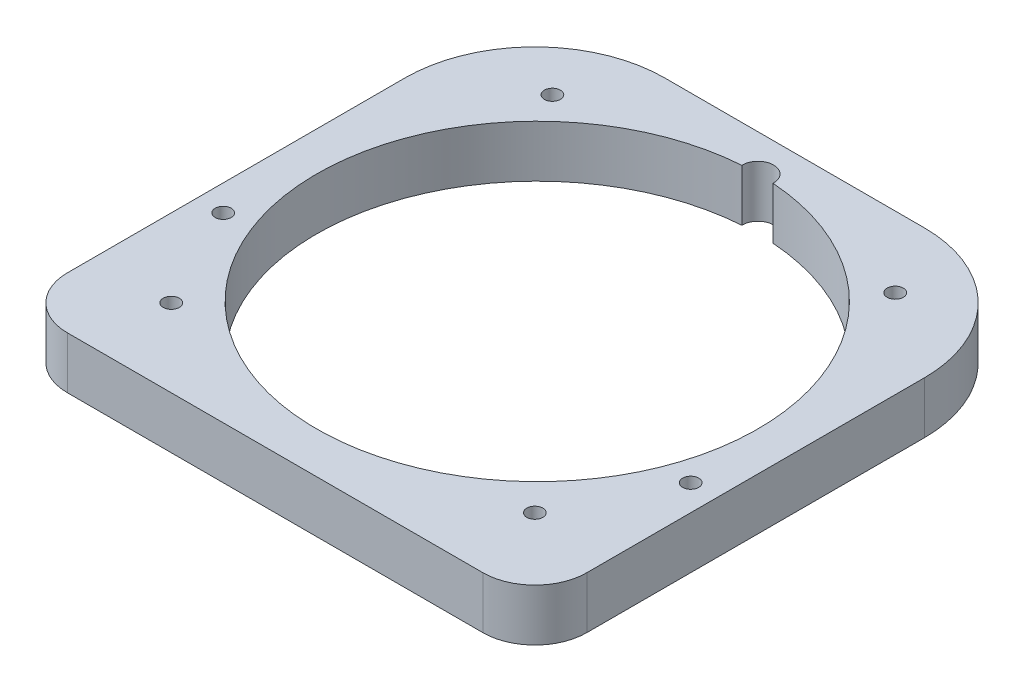
SolidWorks part; units mm, degrees
ref_plane "Płaszczyzna przednia" through (0, 0, 0) normal (0, 0, 1) x (1, 0, 0)
ref_plane "Płaszczyzna górna" through (0, 0, 0) normal (0, 1, 0) x (1, 0, 0)
ref_plane "Płaszczyzna prawa" through (0, 0, 0) normal (1, 0, 0) x (0, 0, -1)
sketch "Szkic1" plane through (0, 0, 0) normal (0, 1, 0) x (1, 0, 0)
  line L8 (10, 0) -> (90, 0)
  line L9 (100, 10) -> (100, 75)
  line L10 (75, 100) -> (25, 100)
  line L11 (0, 75) -> (0, 10)
  arc A8 (90, 0) -> (100, 10) centre (90, 10) ccw
  arc A9 (100, 75) -> (75, 100) centre (75, 75) ccw
  arc A10 (25, 100) -> (0, 75) centre (25, 75) ccw
  arc A11 (0, 10) -> (10, 0) centre (10, 10) ccw
extrude "Dodanie-wyciągnięcie1" add sketch "Szkic1" against normal blind 10
sketch "Szkic4" plane through (0, 0, 0) normal (0, 1, 0) x (1, 0, 0)
  line L0 (50, 15.022) -> (50, 78.4919) construction
  arc A0 (47.0019, 92.856) -> (52.9981, 92.856) centre (50, 50.4619) ccw
  arc A1 (52.9981, 92.856) -> (47.0019, 92.856) centre (50, 92.9619) ccw
  dimension "D3" = 85
  dimension "D4" = 6
  dimension "D1" = 0
  dimension "D2" = 6
extrude "Wytnij-wyciągnięcie2" cut sketch "Szkic4" against normal through all
sketch "Szkic5" plane through (0, 0, 0) normal (0, 1, 0) x (1, 0, 0)
  circle A0 centre (83, 86.3783) radius 1.55 construction
  circle A3 centre (85, 15) radius 1.55 construction
  circle A4 centre (83, 86.3783) radius 1.55
  circle A7 centre (85, 15) radius 1.55
  circle A8 centre (5, 35) radius 1.55
  circle A10 centre (95, 35) radius 1.55
  circle A12 centre (17, 86.3783) radius 1.55
  circle A13 centre (15, 15) radius 1.55
  dimension "D1" = 3.1
  dimension "D2" = 3.1
  dimension "D7" = 3.1
  dimension "D8" = 3.1
extrude "Wytnij-wyciągnięcie3" cut sketch "Szkic5" against normal through all
equation "\"tolerancja_wpusy\"=0.2"
equation "\"dlugosc_wpustu_duzy\"=20"
equation "\"srednica_otworu_M3\"=3.1"
equation "\"szerokosc_nogi_T\"=3.1"
equation "\"dlugosc_T_30\"=11"
equation "\"grubosc_na_nakretke_kwadrat\"=2"
equation "\"szerokosc_na_nakretke_kwadrat\"=5.85"
equation "\"wyokosc_nadstawki_T\"=0.5"
equation "\"dlugosc_T_20_6\"=14"
equation "\"D7@Szkic5\" = \"srednica_otworu_M3\""
equation "\"D8@Szkic5\"=\"srednica_otworu_M3\""
equation "\"D1@Szkic5\"=\"srednica_otworu_M3\""
equation "\"D2@Szkic5\"=\"srednica_otworu_M3\""
